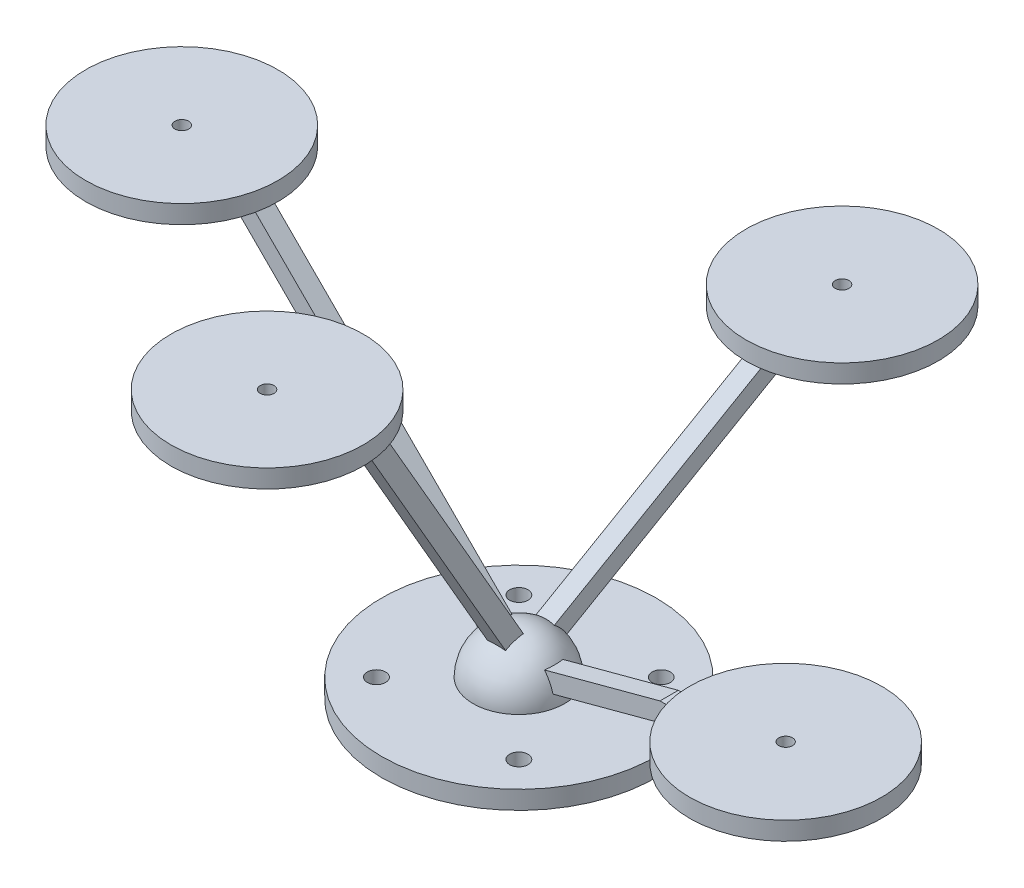
SolidWorks part; units mm, degrees
ref_plane "前视基准面" through (0, 0, 0) normal (0, 0, 1) x (1, 0, 0)
ref_plane "上视基准面" through (0, 0, 0) normal (0, 1, 0) x (1, 0, 0)
ref_plane "右视基准面" through (0, 0, 0) normal (1, 0, 0) x (0, 0, -1)
sketch "草图1" plane through (0, 0, 0) normal (0, 1, 0) x (1, 0, 0)
  line L0 (-23.4221, 0) -> (25.8766, 0) construction
  line L1 (0, 26.1921) -> (0, -25.0701) construction
  line L2 (-18.9498, 18.9498) -> (18.8862, -18.8862) construction
  line L3 (18.9424, 18.9424) -> (-20.2044, -20.2044) construction
  circle A0 centre (0, 0) radius 15
  circle A1 centre (0, 0) radius 11 construction
  circle A2 centre (7.7782, 7.7782) radius 1
  circle A3 centre (-7.7782, 7.7782) radius 1
  circle A4 centre (-7.7782, -7.7782) radius 1
  circle A5 centre (7.7782, -7.7782) radius 1
  dimension "D1" = 30
  dimension "D4" = 22
  dimension "D5" = 2
  dimension "D2" = 45
  dimension "D3" = 45
extrude "凸台-拉伸1" add sketch "草图1" along normal blind 2
sketch "草图2" plane through (0, 0, 0) normal (1, 0, 0) x (0, 0, -1)
  line L0 (0, 2) -> (0, 7)
  line L1 (15, 2) -> (-15, 2) construction
  line L2 (0, 2) -> (5, 2)
  arc A0 (0, 7) -> (5, 2) centre (0, 2) cw
  dimension "D1" = 5
revolve "旋转1" add sketch "草图2" angle 360 about L0
sketch "草图3" plane through (0, 0, 0) normal (0, 0, 1) x (1, 0, 0)
  line L0 (0, 2) -> (0, 9.7216) construction
  line L1 (15, 2) -> (-15, 2) construction
  line L2 (0, 2) -> (24.1481, 8.4705)
  line L3 (8.7782, 2) -> (6.7782, 2) construction
  line L4 (0, 4.0706) -> (16.4207, 8.4705)
  line L6 (16.4207, 8.4705) -> (24.1481, 8.4705)
  line L7 (0, 2) -> (-31.8198, 33.8198)
  line L8 (-28.9914, 33.8198) -> (0, 4.8284)
  line L9 (0, 4.8284) -> (0, 4.0706)
  line L10 (-31.8198, 33.8198) -> (-28.9914, 33.8198)
  point P14 (0, 0)
  dimension "D1" = 15
  dimension "D2" = 25
  dimension "D3" = 2
  dimension "D4" = 45
  dimension "D5" = 45
  dimension "D6" = 2
extrude "凸台-拉伸2" add sketch "草图3" along normal mid plane 2
sketch "草图4" plane through (0, 8.4705, 0) normal (0, 1, 0) x (1, 0, 0)
  line L0 (24.1481, -1) -> (24.1481, 1) construction
  circle A0 centre (29.1481, 0) radius 10.5
  circle A1 centre (29.1481, 0) radius 0.75
  dimension "D1" = 21
  dimension "D2" = 1.5
  dimension "D3" = 5
extrude "凸台-拉伸3" add sketch "草图4" along normal blind 2
sketch "草图5" plane through (0, 33.8198, 0) normal (0, 1, 0) x (1, 0, 0)
  line L0 (-31.8198, -1) -> (-31.8198, 1) construction
  circle A0 centre (-36.8198, 0) radius 10.5
  circle A1 centre (-36.8198, 0) radius 0.75
  point P2 (0, 0)
  dimension "D1" = 21
  dimension "D2" = 1.5
  dimension "D3" = 5
extrude "凸台-拉伸4" add sketch "草图5" along normal blind 2
sketch "草图6" plane through (0, 0, 0) normal (1, 0, 0) x (0, 0, -1)
  line L0 (0, 0) -> (0, 10.6928) construction
  line L1 (0, 2) -> (30.3109, 19.5)
  line L2 (15, 2) -> (-15, 2) construction
  line L3 (8.7782, 2) -> (6.7782, 2) construction
  line L4 (0, 4.3094) -> (26.3109, 19.5)
  line L5 (26.3109, 19.5) -> (30.3109, 19.5)
  line L6 (0, 2) -> (-22.5, 40.9711)
  line L7 (0, 6) -> (-20.1906, 40.9711)
  line L8 (-22.5, 40.9711) -> (-20.1906, 40.9711)
  line L9 (0, 6) -> (0, 4.3094)
  dimension "D1" = 30
  dimension "D2" = 35
  dimension "D3" = 2
  dimension "D4" = 60
  dimension "D5" = 45
  dimension "D6" = 2
extrude "凸台-拉伸5" add sketch "草图6" along normal mid plane 2
sketch "草图7" plane through (0, 19.5, 0) normal (0, 1, 0) x (1, 0, 0)
  line L0 (1, 30.3109) -> (-1, 30.3109) construction
  circle A0 centre (0, 35.3109) radius 10.5
  circle A1 centre (0, 35.3109) radius 0.75
  point P4 (0, 0)
  point P5 (0, 0)
  dimension "D1" = 21
  dimension "D2" = 1.5
  dimension "D3" = 5
extrude "凸台-拉伸6" add sketch "草图7" along normal blind 2
sketch "草图8" plane through (0, 40.9711, 0) normal (0, 1, 0) x (1, 0, 0)
  line L0 (1, -22.5) -> (-1, -22.5) construction
  circle A0 centre (0, -27.5) radius 10.5
  circle A1 centre (0, -27.5) radius 0.75
  point P5 (0, 0)
  dimension "D1" = 1.5
  dimension "D2" = 21
  dimension "D3" = 5
extrude "凸台-拉伸7" add sketch "草图8" along normal blind 2
